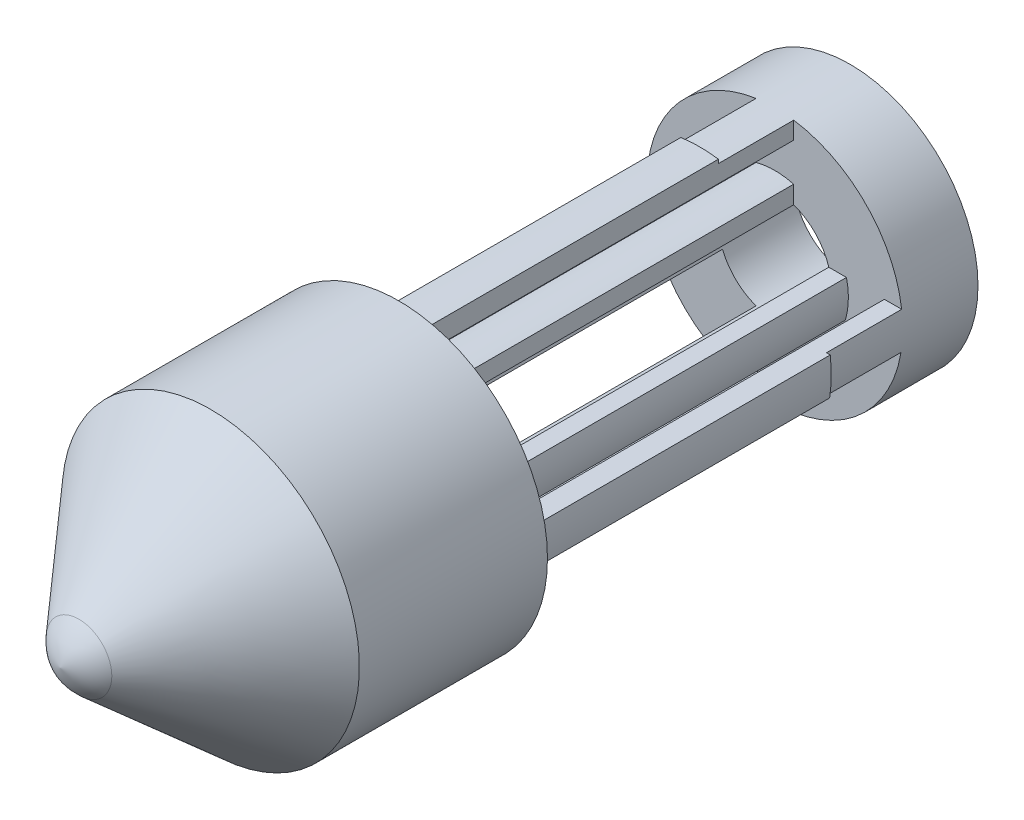
SolidWorks part; units mm, degrees
ref_plane "Alzado" through (0, 0, 0) normal (0, 0, 1) x (1, 0, 0)
ref_plane "Planta" through (0, 0, 0) normal (0, 1, 0) x (1, 0, 0)
ref_plane "Vista lateral" through (0, 0, 0) normal (1, 0, 0) x (0, 0, -1)
sketch "Croquis1" plane through (0, 0, 0) normal (0, 0, 1) x (1, 0, 0)
  circle A0 centre (0, 0) radius 7
  circle A1 centre (0, 0) radius 3
  dimension "D1" = 6
extrude "Saliente-Extruir1" add sketch "Croquis1" along normal blind 1
sketch "Croquis2" plane through (0, 0, 1) normal (0, 0, 1) x (1, 0, 0)
  circle A2 centre (0, 0) radius 7 construction
  circle A3 centre (0, 0) radius 7
  circle A4 centre (0, 0) radius 5
  circle A7 centre (0, 0) radius 3
  circle A9 centre (0, 0) radius 3
  circle M3 centre (0, 0) radius 7
  dimension "D1" = 2
  dimension "D2" = 2
extrude "Saliente-Extruir2" add sketch "Croquis2" along normal blind 3 contours A4 M3 | A7 A9
sketch "Croquis3" plane through (0, 0, 4) normal (0, 0, 1) x (1, 0, 0)
  line L0 (-5.8218, 0.8853) -> (-6.9438, 0.8853)
  line L1 (-5.8887, 0) -> (-12.4279, 0) construction
  line L2 (-3.7447, -1.1144) -> (-2.7853, -1.1144)
  line L3 (0, -3) -> (0, -3.907) construction
  line L4 (6.9438, 0.8853) -> (5.8218, 0.8853)
  line L5 (-6.9107, -1.1144) -> (-5.7823, -1.1144)
  line L6 (-1, 6.9282) -> (-1, 5.8032)
  line L7 (1, -6.9282) -> (1, -5.8032)
  line L8 (1, 5.8032) -> (1, 6.9282)
  line L9 (0, 5.8887) -> (0, 10.8197) construction
  line L10 (-1, 3.7769) -> (-1, 2.8284)
  line L11 (3.8054, 0.8853) -> (2.8664, 0.8853)
  line L12 (5.8887, 0) -> (13.2079, 0) construction
  line L13 (5.7823, -1.1144) -> (6.9107, -1.1144)
  line L14 (1, -3.7769) -> (1, -2.8284)
  line L15 (0, -5.8887) -> (0, -12.5246) construction
  line L16 (-1, -5.8032) -> (-1, -6.9282)
  line L18 (2.7853, -1.1144) -> (3.7447, -1.1144)
  line L19 (-1, -2.8284) -> (-1, -3.7769)
  line L20 (-3, 0) -> (-3.907, 0) construction
  line L21 (-2.8664, 0.8853) -> (-3.8054, 0.8853)
  line L23 (0, 3) -> (0, 3.907) construction
  line L25 (1, 2.8284) -> (1, 3.7769)
  line L26 (3, 0) -> (3.907, 0) construction
  arc A0 (6.9107, -1.1144) -> (6.9438, 0.8853) centre (0, 0) ccw
  circle A1 centre (0, 0) radius 7
  arc A2 (1, 6.9282) -> (-1, 6.9282) centre (0, 0) ccw
  arc A3 (-1, -6.9282) -> (1, -6.9282) centre (0, 0) ccw
  arc A4 (-6.9438, 0.8853) -> (-6.9107, -1.1144) centre (0, 0) ccw
  arc A5 (-5.8218, 0.8853) -> (-5.7823, -1.1144) centre (0, 0) ccw
  arc A6 (-3.8054, 0.8853) -> (-3.7447, -1.1144) centre (0, 0) ccw
  arc A7 (-2.8664, 0.8853) -> (-2.7853, -1.1144) centre (0, 0) ccw
  arc A8 (1, 5.8032) -> (-1, 5.8032) centre (0, 0) ccw
  arc A9 (1, 3.7769) -> (-1, 3.7769) centre (0, 0) ccw
  arc A10 (1, 2.8284) -> (-1, 2.8284) centre (0, 0) ccw
  arc A11 (5.7823, -1.1144) -> (5.8218, 0.8853) centre (0, 0) ccw
  arc A12 (3.7447, -1.1144) -> (3.8054, 0.8853) centre (0, 0) ccw
  arc A13 (2.7853, -1.1144) -> (2.8664, 0.8853) centre (0, 0) ccw
  arc A14 (-1, -5.8032) -> (1, -5.8032) centre (0, 0) ccw
  arc A15 (-1, -3.7769) -> (1, -3.7769) centre (0, 0) ccw
  arc A16 (-1, -2.8284) -> (1, -2.8284) centre (0, 0) ccw
  dimension "D2" = 2
  dimension "D3" = 2
  dimension "D1" = 0
extrude "Saliente-Extruir4" add sketch "Croquis3" along normal blind 30
ref_plane "Plano1" through (0, 0, 24) normal (0, 0, 1) x (1, 0, 0)
sketch "Croquis6" plane through (0, 0, 24) normal (0, 0, 1) x (1, 0, 0)
  line L4 (-5.4616, 1.1853) -> (-7.2031, 1.1853)
  line L5 (-7.1617, -1.4144) -> (-5.4068, -1.4144)
  line L6 (-5.4616, 1.1853) -> (-7.2031, 1.1853)
  line L7 (-7.1617, -1.4144) -> (-5.4068, -1.4144)
  line L12 (-1.3, -5.4354) -> (-1.3, -7.1833)
  line L13 (1.3, -7.1833) -> (1.3, -5.4354)
  line L14 (-1.3, -5.4354) -> (-1.3, -7.1833)
  line L15 (1.3, -7.1833) -> (1.3, -5.4354)
  line L18 (5.4068, -1.4144) -> (7.1617, -1.4144)
  line L19 (7.2031, 1.1853) -> (5.4616, 1.1853)
  line L20 (5.4068, -1.4144) -> (7.1617, -1.4144)
  line L21 (7.2031, 1.1853) -> (5.4616, 1.1853)
  line L24 (1.3, 5.4354) -> (1.3, 7.1833)
  line L25 (-1.3, 7.1833) -> (-1.3, 5.4354)
  line L26 (1.3, 5.4354) -> (1.3, 7.1833)
  line L27 (-1.3, 7.1833) -> (-1.3, 5.4354)
  line L30 (-3.9621, -1.4144) -> (-2.2999, -1.4144)
  line L31 (-2.4259, 1.1853) -> (-4.0366, 1.1853)
  line L32 (-3.9621, -1.4144) -> (-2.2999, -1.4144)
  line L33 (-2.4259, 1.1853) -> (-4.0366, 1.1853)
  line L36 (-1.3, 4.0012) -> (-1.3, 2.3664)
  line L37 (1.3, 2.3664) -> (1.3, 4.0012)
  line L38 (-1.3, 4.0012) -> (-1.3, 2.3664)
  line L39 (1.3, 2.3664) -> (1.3, 4.0012)
  line L42 (4.0366, 1.1853) -> (2.4259, 1.1853)
  line L43 (2.2999, -1.4144) -> (3.9621, -1.4144)
  line L44 (4.0366, 1.1853) -> (2.4259, 1.1853)
  line L45 (2.2999, -1.4144) -> (3.9621, -1.4144)
  line L48 (1.3, -4.0012) -> (1.3, -2.3664)
  line L49 (-1.3, -2.3664) -> (-1.3, -4.0012)
  line L50 (1.3, -4.0012) -> (1.3, -2.3664)
  line L51 (-1.3, -2.3664) -> (-1.3, -4.0012)
  circle A0 centre (0, 0) radius 7.907
  arc A5 (-7.2031, 1.1853) -> (-7.1617, -1.4144) centre (0, 0) ccw
  arc A6 (-5.4616, 1.1853) -> (-5.4068, -1.4144) centre (0, 0) ccw
  arc A13 (-1.3, -7.1833) -> (1.3, -7.1833) centre (0, 0) ccw
  arc A14 (-1.3, -5.4354) -> (1.3, -5.4354) centre (0, 0) ccw
  arc A19 (7.1617, -1.4144) -> (7.2031, 1.1853) centre (0, 0) ccw
  arc A20 (5.4068, -1.4144) -> (5.4616, 1.1853) centre (0, 0) ccw
  arc A22 (5.4068, -1.4144) -> (5.4616, 1.1853) centre (0, 0) ccw
  arc A25 (1.3, 7.1833) -> (-1.3, 7.1833) centre (0, 0) ccw
  arc A26 (1.3, 5.4354) -> (-1.3, 5.4354) centre (0, 0) ccw
  arc A31 (-4.0366, 1.1853) -> (-3.9621, -1.4144) centre (0, 0) ccw
  arc A32 (-2.4259, 1.1853) -> (-2.2999, -1.4144) centre (0, 0) ccw
  arc A34 (-2.4259, 1.1853) -> (-2.2999, -1.4144) centre (0, 0) ccw
  arc A37 (1.3, 4.0012) -> (-1.3, 4.0012) centre (0, 0) ccw
  arc A38 (1.3, 2.3664) -> (-1.3, 2.3664) centre (0, 0) ccw
  arc A39 (1.3, 4.0012) -> (-1.3, 4.0012) centre (0, 0) ccw
  arc A40 (1.3, 2.3664) -> (-1.3, 2.3664) centre (0, 0) ccw
  arc A43 (3.9621, -1.4144) -> (4.0366, 1.1853) centre (0, 0) ccw
  arc A44 (2.2999, -1.4144) -> (2.4259, 1.1853) centre (0, 0) ccw
  arc A46 (2.2999, -1.4144) -> (2.4259, 1.1853) centre (0, 0) ccw
  arc A49 (-1.3, -4.0012) -> (1.3, -4.0012) centre (0, 0) ccw
  arc A50 (-1.3, -2.3664) -> (1.3, -2.3664) centre (0, 0) ccw
  arc A52 (-1.3, -2.3664) -> (1.3, -2.3664) centre (0, 0) ccw
  arc A53 (-5.4616, 1.1853) -> (-5.4068, -1.4144) centre (0, 0) ccw
  arc A54 (-1.3, -5.4354) -> (1.3, -5.4354) centre (0, 0) ccw
  arc A55 (1.3, 5.4354) -> (-1.3, 5.4354) centre (0, 0) ccw
  arc A56 (-4.0366, 1.1853) -> (-3.9621, -1.4144) centre (0, 0) ccw
  arc A57 (3.9621, -1.4144) -> (4.0366, 1.1853) centre (0, 0) ccw
  arc A58 (-1.3, -4.0012) -> (1.3, -4.0012) centre (0, 0) ccw
  arc A59 (-7.2031, 1.1853) -> (-7.1617, -1.4144) centre (0, 0) ccw
  arc A60 (-1.3, -7.1833) -> (1.3, -7.1833) centre (0, 0) ccw
  arc A61 (7.1617, -1.4144) -> (7.2031, 1.1853) centre (0, 0) ccw
  arc A62 (1.3, 7.1833) -> (-1.3, 7.1833) centre (0, 0) ccw
  dimension "D1" = 0.3
  dimension "D2" = 0.3
  dimension "D3" = 0.3
  dimension "D4" = 0.3
  dimension "D5" = 0.3
  dimension "D6" = 0.3
  dimension "D7" = 0.3
  dimension "D8" = 0.3
extrude "Saliente-Extruir6" add sketch "Croquis6" along normal blind 10 separate body
sketch "Croquis7" plane through (0, 0, 0) normal (0, 1, 0) x (1, 0, 0)
  line L0 (0, -34) -> (7.907, -34)
  line L1 (-1.3, -34) -> (1.3, -34) construction
  line L2 (-7.907, -34) -> (7.907, -34) construction
  line L3 (7.907, -34) -> (1.7486, -41.0064)
  line L4 (0, -41.9995) -> (0, -34)
  arc A0 (1.7486, -41.0064) -> (0, -41.9995) centre (-0.5606, -38.9766) cw
revolve "Revolución1" add sketch "Croquis7" angle 360 about L4
sketch "Croquis8" plane through (0, 0, 0) normal (0, 0, -1) x (-1, 0, 0)
  circle A4 centre (0, 0) radius 6.8
  circle A5 centre (0, 0) radius 6.8
  circle A6 centre (0, 0) radius 7
  circle A7 centre (0, 0) radius 7
  dimension "D1" = 0.2
  dimension "D2" = 0
extrude "Cortar-Extruir2" cut sketch "Croquis8" against normal blind 8
